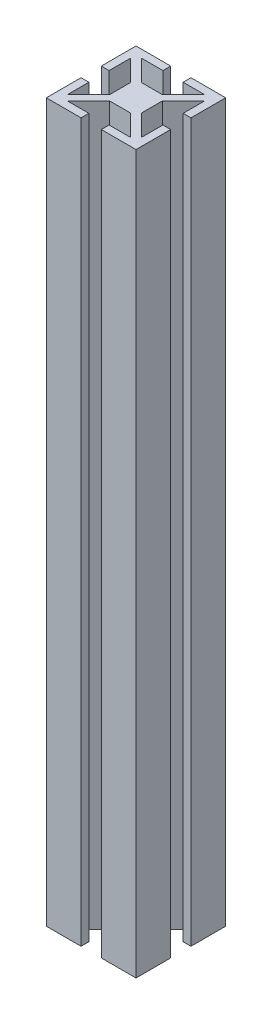
SolidWorks part; units mm, degrees
ref_plane "Front Plane" through (0, 0, 0) normal (0, 0, 1) x (1, 0, 0)
ref_plane "Top Plane" through (0, 0, 0) normal (0, 1, 0) x (1, 0, 0)
ref_plane "Right Plane" through (0, 0, 0) normal (1, 0, 0) x (0, 0, -1)
sketch "Sketch1" plane through (11.365, 0, 9.8462) normal (0, 1, 0) x (1, 0, 0)
  line L0 (-11.365, 9.8462) -> (-11.365, 32.3924) construction
  line L1 (-11.365, 9.8462) -> (-35.43, 9.8462) construction
  line L2 (-11.365, 9.8462) -> (-7.5972, 6.0784) construction
  line L3 (-24.065, 22.5462) -> (-14.2298, 22.5462)
  line L4 (-14.2298, 22.5462) -> (-14.2298, 20.3364)
  line L5 (-14.2298, 20.3364) -> (-20.2926, 20.3364)
  line L6 (-20.2926, 20.3364) -> (-14.3109, 14.3547)
  line L7 (-14.3109, 14.3547) -> (-8.4191, 14.3547)
  line L8 (-15.8735, 12.7921) -> (-15.8735, 6.9003)
  line L9 (-21.8552, 18.7738) -> (-15.8735, 12.7921)
  line L10 (-21.8552, 12.711) -> (-21.8552, 18.7738)
  line L11 (-24.065, 12.711) -> (-21.8552, 12.711)
  line L12 (-24.065, 22.5462) -> (-24.065, 12.711)
  line L13 (-14.3109, 5.3377) -> (-8.4191, 5.3377)
  line L14 (-20.2926, -0.644) -> (-14.3109, 5.3377)
  line L15 (-21.8552, 0.9186) -> (-15.8735, 6.9003)
  line L16 (-21.8552, 6.9814) -> (-21.8552, 0.9186)
  line L17 (-24.065, 6.9814) -> (-21.8552, 6.9814)
  line L18 (-24.065, -2.8538) -> (-24.065, 6.9814)
  line L19 (-14.2298, -0.644) -> (-20.2926, -0.644)
  line L20 (-14.2298, -2.8538) -> (-14.2298, -0.644)
  line L21 (-24.065, -2.8538) -> (-14.2298, -2.8538)
  line L22 (1.335, -2.8538) -> (-8.5002, -2.8538)
  line L23 (-8.5002, -2.8538) -> (-8.5002, -0.644)
  line L24 (-8.5002, -0.644) -> (-2.4374, -0.644)
  line L25 (1.335, -2.8538) -> (1.335, 6.9814)
  line L26 (1.335, 6.9814) -> (-0.8748, 6.9814)
  line L27 (-0.8748, 6.9814) -> (-0.8748, 0.9186)
  line L28 (-0.8748, 0.9186) -> (-6.8565, 6.9003)
  line L29 (-2.4374, -0.644) -> (-8.4191, 5.3377)
  line L30 (1.335, 22.5462) -> (1.335, 12.711)
  line L31 (1.335, 12.711) -> (-0.8748, 12.711)
  line L32 (-0.8748, 12.711) -> (-0.8748, 18.7738)
  line L33 (-0.8748, 18.7738) -> (-6.8565, 12.7921)
  line L34 (-6.8565, 12.7921) -> (-6.8565, 6.9003)
  line L35 (-2.4374, 20.3364) -> (-8.4191, 14.3547)
  line L36 (-8.5002, 20.3364) -> (-2.4374, 20.3364)
  line L37 (-8.5002, 22.5462) -> (-8.5002, 20.3364)
  line L38 (1.335, 22.5462) -> (-8.5002, 22.5462)
  point P20 (-15.8735, 9.8462)
  point P26 (-6.8565, 9.8462)
  point P36 (-11.365, 5.3377)
  point P42 (-11.365, 14.3547)
  dimension "D1" = 9.8352
  dimension "D2" = 12.7
  dimension "D3" = 4.5085
  dimension "D4" = 2.2098
  dimension "D5" = 1.1049
extrude "Boss-Extrude1" add sketch "Sketch1" along normal up to surface (203.2 mm away)
other "1010<1>"
